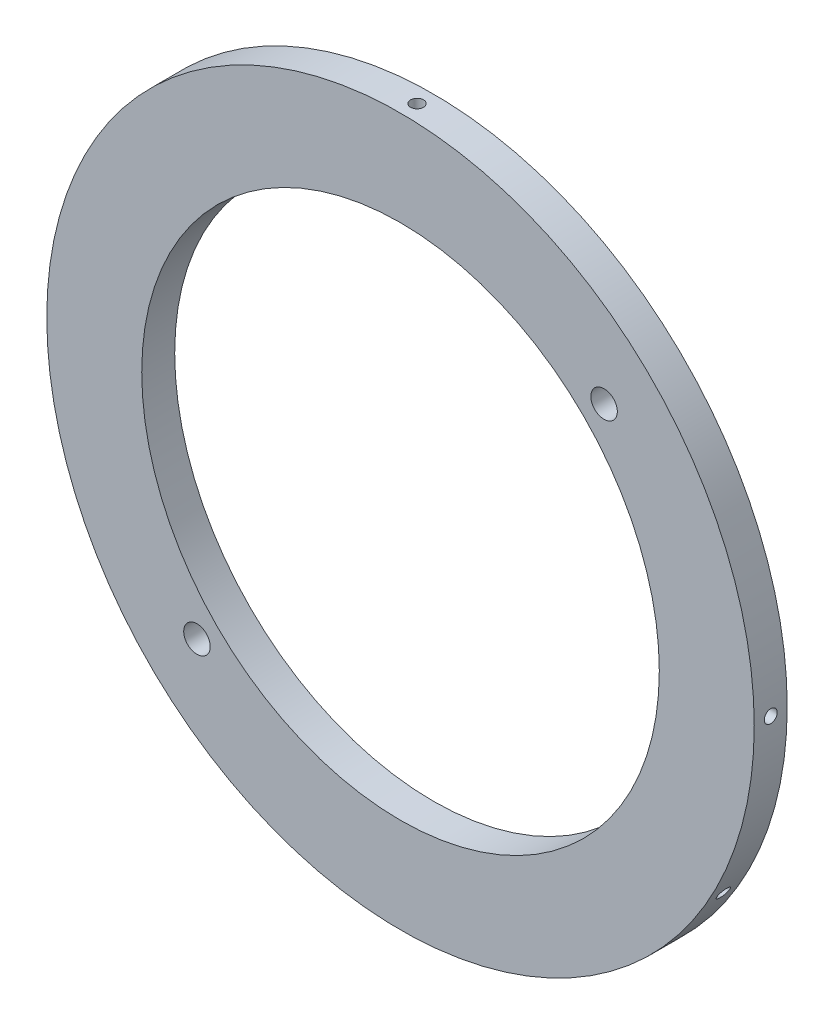
SolidWorks part; units mm, degrees
material "6061-T6 (SS)"
ref_plane "Front Plane" through (0, 0, 0) normal (0, 0, 1) x (1, 0, 0)
ref_plane "Top Plane" through (0, 0, 0) normal (0, 1, 0) x (1, 0, 0)
ref_plane "Right Plane" through (0, 0, 0) normal (1, 0, 0) x (0, 0, -1)
sketch "Sketch1" plane through (0, 0, 0) normal (0, 0, 1) x (1, 0, 0)
  circle A0 centre (0, 0) radius 68.1355
  circle A1 centre (0, 0) radius 49.8475
  dimension "D1" = 136.271
  dimension "D2" = 99.695
extrude "Extrude1" add sketch "Sketch1" along normal blind 6.35
ref_plane "Plane1" through (0, 0, 3.175) normal (0, 0, 1) x (1, 0, 0)
sketch "Sketch3" plane through (0, 0, 3.175) normal (0, 0, 1) x (1, 0, 0)
  line L0 (0, 0) -> (0, 68.1355) construction
  line L1 (0, 0) -> (26.0743, 62.949) construction
  circle A0 centre (0, 0) radius 68.1355 construction
  arc A1 (0, 68.1355) -> (26.0743, 62.949) centre (0, 0) cw
  circle A2 centre (0, 0) radius 55.4355
  arc A3 (0, 55.4355) -> (39.1988, 39.1988) centre (0, 0) cw
ref_plane "Plane3" through (26.0743, 62.949, 3.175) normal (0.3827, 0.9239, 0) x (-0.9239, 0.3827, 0)
ref_plane "Plane2" through (0, 68.1355, 3.175) normal (0, 1, 0) x (-1, 0, 0)
hole_wizard "M3x0.5 Tapped Hole1" positions "Sketch5" profile "Sketch4" tap size "M3x0.5" standard "Ansi Metric"
sketch "Sketch5" plane through (0, 68.1355, 3.175) normal (0, 1, 0) x (-1, 0, 0)
  point P1 (0, 0)
sketch "Sketch4" plane through (0, 68.1355, 3.175) normal (1, 0, 0) x (0, 0, 1)
  line L0 (0, 0) -> (0, 9.3871)
  line L1 (0, 9.3871) -> (1.25, 8.636)
  line L2 (1.25, 8.636) -> (1.25, 0)
  line L5 (1.25, 0) -> (0, 0)
  line L10 (0, 9.3871) -> (-1.25, 8.636) construction
  line L11 (0, -6.35) -> (0, 107.95) construction
  dimension "Tap Drill Dia." = 2.5
  dimension "Tap Drill Depth" = 8.636
  dimension "Drill Angle" = 118
cosmetic thread "Hole Thread1" parameters "D1"=6.096, "D2"=3
pattern_circular "CirPattern1" count 4 over 360 about axis through (0, 0, 6.35) along (0, 0, -1) of "M3x0.5 Tapped Hole1"
pattern_circular "CirPattern3" count 3 over 360 about axis through (0, 0, 6.35) along (0, 0, -1) of "M3x0.5 Tapped Hole1"
sketch "Sketch17" plane through (0, 0, 6.35) normal (0, 0, 1) x (1, 0, 0)
  line L0 (0, 0) -> (39.2078, 39.2078) construction
  line L1 (0, 0) -> (0, 76.7349) construction
  line L2 (0, 59.4995) -> (0, 68.1355) construction
  line L3 (0, 59.4995) -> (0, 58.7484) construction
  dimension "D1" = 55.4482
  dimension "D2" = 45
hole_wizard "1/4-20 Tapped Hole1" positions "3DSketch1" profile "Sketch18" tap size "1/4-20" standard "Ansi Inch"
sketch3d "3DSketch1"
  point P0 (39.2078, 39.2078, 6.35)
sketch "Sketch18" plane through (39.2078, 39.2078, 6.35) normal (1, 0, 0) x (0, -1, 0)
  line L0 (0, 0) -> (0, 20.5838)
  line L1 (0, 20.5838) -> (2.5527, 19.05)
  line L2 (2.5527, 19.05) -> (2.5527, 0)
  line L5 (2.5527, 0) -> (0, 0)
  line L10 (0, 20.5838) -> (-2.5527, 19.05) construction
  line L11 (0, -6.35) -> (0, 107.95) construction
  dimension "Tap Drill Dia." = 5.1054
  dimension "Tap Drill Depth" = 19.05
  dimension "Drill Angle" = 118
cosmetic thread "Hole Thread2" parameters "D1"=6.35, "D2"=6.35
pattern_circular "CirPattern2" count 2 over 360 about axis through (0, 0, 0) along (0, 0, 1) of "1/4-20 Tapped Hole1"
